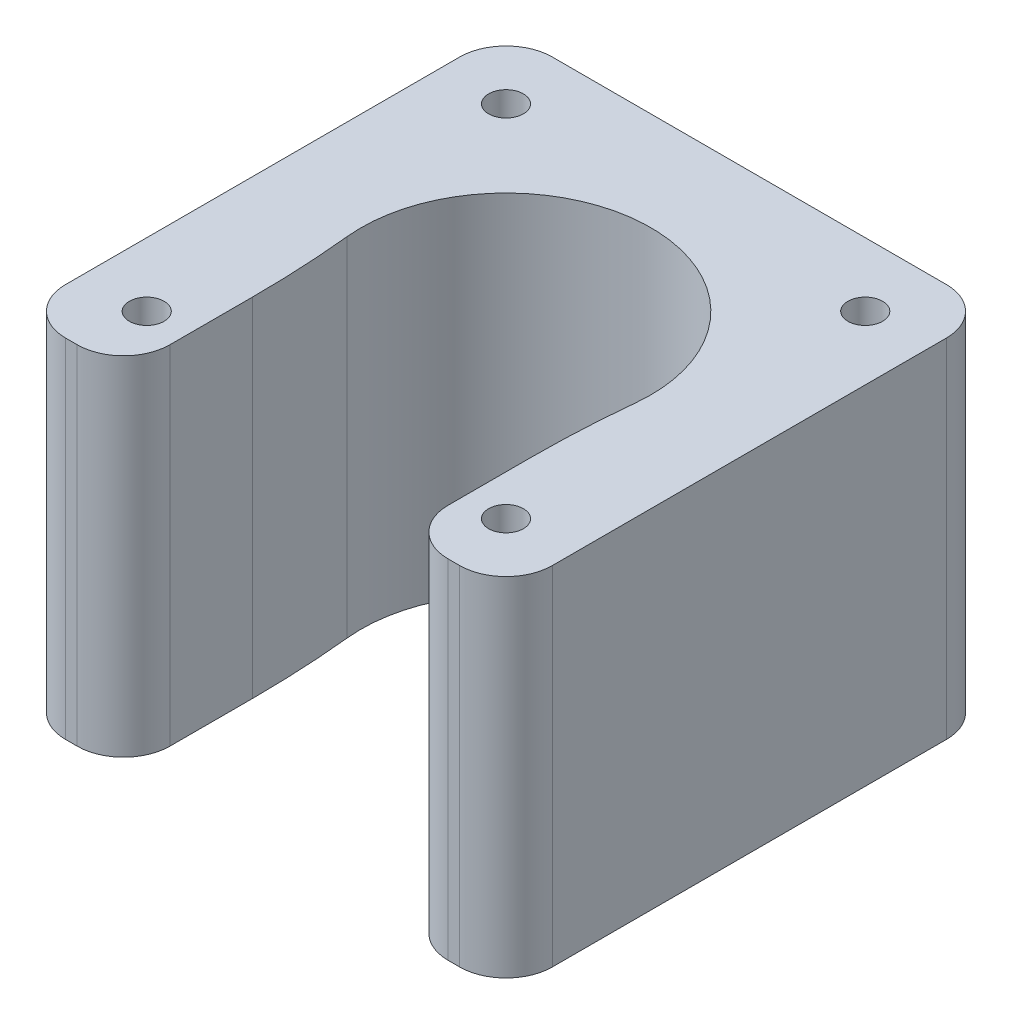
SolidWorks part; units mm, degrees
material "ABS PC"
ref_plane "Front Plane" through (0, 0, 0) normal (0, 0, 1) x (1, 0, 0)
ref_plane "Top Plane" through (0, 0, 0) normal (0, 1, 0) x (1, 0, 0)
ref_plane "Right Plane" through (0, 0, 0) normal (1, 0, 0) x (0, 0, -1)
sketch "Sketch1" plane through (0, 0, 0) normal (0, 1, 0) x (1, 0, 0)
  line L0 (0, -12.5) -> (0, -15.5)
  line L1 (-21, -21) -> (21, -21)
  line L2 (-21, -21) -> (-21, 21)
  line L3 (-21, 21) -> (21, 21)
  line L4 (21, -21) -> (21, 21)
  line L5 (-21, -21) -> (21, 21) construction
  line L6 (-21, 21) -> (21, -21) construction
  line L7 (-15.5, -15.5) -> (15.5, -15.5)
  line L8 (-15.5, -15.5) -> (-15.5, 15.5)
  line L9 (-15.5, 15.5) -> (15.5, 15.5)
  line L10 (15.5, -15.5) -> (15.5, 15.5)
  line L11 (-15.5, -15.5) -> (15.5, 15.5) construction
  line L12 (-15.5, 15.5) -> (15.5, -15.5) construction
  line L13 (15.5, -15.5) -> (12, -15.5)
  line L14 (12, -15.5) -> (12, -3.5)
  line L15 (-15.5, -15.5) -> (-12, -15.5)
  line L16 (-12, -15.5) -> (-12, -3.5)
  line L17 (-12, -15.5) -> (-12, -21)
  line L18 (12, -15.5) -> (12, -21)
  circle A0 centre (0, 0) radius 12.5
  circle A1 centre (-15.5, 15.5) radius 1.5
  circle A2 centre (15.5, 15.5) radius 1.5
  circle A3 centre (15.5, -15.5) radius 1.5
  circle A4 centre (-15.5, -15.5) radius 1.5
  point P0 (0, 0)
  dimension "D1" = 42
  dimension "D2" = 25
  dimension "D3" = 3
  dimension "D4" = 31
  dimension "D5" = 3.5
  dimension "D6" = 3.5
extrude "Boss-Extrude1" add sketch "Sketch1" along normal blind 30 contours A4 L8 A1 L9 A2 L10 A3 L7 L18 L1 L4 L3 L2 L17 L15 | A4 L15 L16 A0 L14 L7 A3 L10 A2 L9 A1 L8
fillet "Fillet1" radius 85 2 edges at (-12, 15, 3.5) (12, 15, 3.5)
fillet "Fillet2" radius 4 6 edges at (-21, 15, 21) (-12, 15, 21) (21, 15, 21) (12, 15, 21) (-21, 15, -21) (21, 15, -21)
